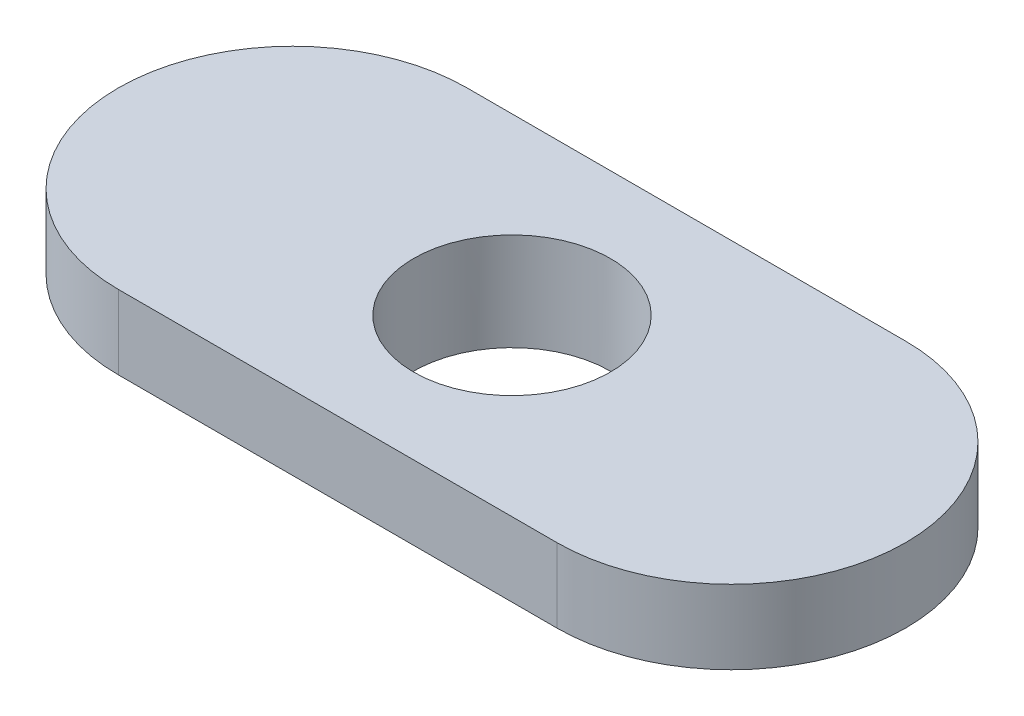
SolidWorks part; units mm, degrees
ref_plane "Front Plane" through (0, 0, 0) normal (0, 0, 1) x (1, 0, 0)
ref_plane "Top Plane" through (0, 0, 0) normal (0, 1, 0) x (1, 0, 0)
ref_plane "Right Plane" through (0, 0, 0) normal (1, 0, 0) x (0, 0, -1)
sketch "Sketch1" plane through (0, 0, 0) normal (0, 1, 0) x (1, 0, 0)
  circle A0 centre (0, 0) radius 3.175
  point P3 (-3.175, 0)
  point P4 (3.175, 0)
  dimension "D1" = 6.35
sketch "Sketch8" plane through (0, 0, 0) normal (0, 1, 0) x (1, 0, 0)
  line L0 (-7.0739, 0) -> (7.0739, 0) construction
  line L1 (-7.0739, 5.6261) -> (7.0739, 5.6261)
  line L2 (-7.0739, -5.6261) -> (7.0739, -5.6261)
  line L4 (-12.7, 5.6261) -> (12.7, 5.6261) construction
  line L5 (-12.7, 5.6261) -> (-12.7, -5.6261) construction
  line L6 (-12.7, -5.6261) -> (12.7, -5.6261) construction
  line L7 (12.7, 5.6261) -> (12.7, -5.6261) construction
  arc A0 (-7.0739, 5.6261) -> (-7.0739, -5.6261) centre (-7.0739, 0) ccw
  arc A1 (7.0739, -5.6261) -> (7.0739, 5.6261) centre (7.0739, 0) ccw
  circle A3 centre (0, 0) radius 3.175
  circle A4 centre (0, 0) radius 3.175
  point P2 (0, 0)
  dimension "D2" = 25.4
  dimension "D3" = 11.2522
  dimension "D1" = 0
extrude "Boss-Extrude2" add sketch "Sketch8" against normal blind 2.3876 from offset 6.35 separate body offset against normal yes
sketch "Sketch9" plane through (0, -8.7376, 0) normal (0, -1, 0) x (1, 0, 0)
  circle A1 centre (0, 0) radius 3.175 construction
  circle A2 centre (0, 0) radius 3.175
  circle A3 centre (0, 0) radius 3.5687
  dimension "D1" = 7.1374
extrude "Boss-Extrude3" add sketch "Sketch9" along normal blind 0.762
equation "\"D3@Helix/Spiral1\" = \"D4@Helix/Spiral1\" + \"D1@Boss-Extrude1\""
equation "\"D1@Sketch3\" = \"D4@Helix/Spiral1\""
equation "\"D2@Sketch3\" = \"D1@Sketch3\" / 8"
equation "\"D1@Cut-Extrude1\" = \"D4@Helix/Spiral1\""
equation "\"D1@Cut-Extrude2\" = \"D1@Sketch6\" * 3/5"
equation "\"D1@Cut-Extrude3\" = \"D1@Cut-Extrude2\""
equation "\"D2@Sketch5\" = \"D1@Sketch5\" * 1/4"
